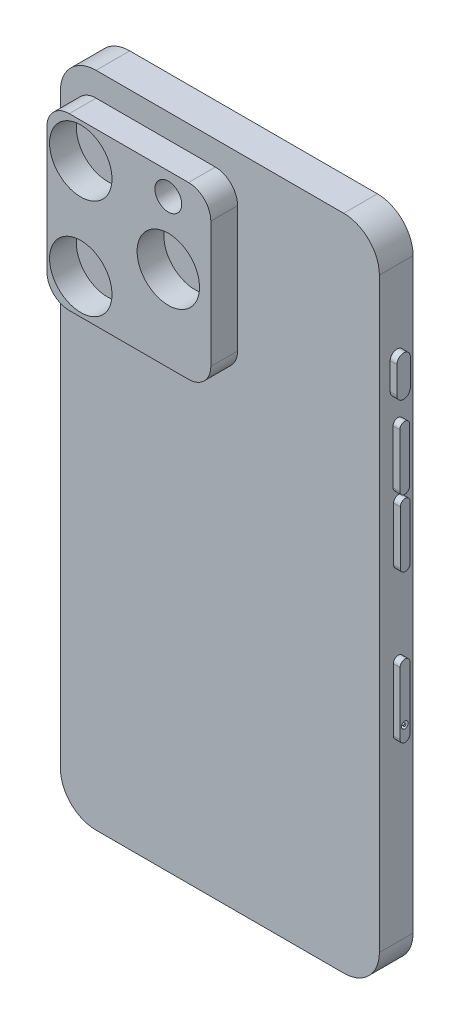
SolidWorks part; units mm, degrees
ref_plane "Front Plane" through (0, 0, 0) normal (0, 0, 1) x (1, 0, 0)
ref_plane "Top Plane" through (0, 0, 0) normal (0, 1, 0) x (1, 0, 0)
ref_plane "Right Plane" through (0, 0, 0) normal (1, 0, 0) x (0, 0, -1)
sketch "Sketch2" plane through (0, 0, 0) normal (0, 0, 1) x (1, 0, 0)
  line L1 (-27.75, 73.75) -> (27.75, 73.75)
  line L2 (-35.75, 65.75) -> (-35.75, -65.75)
  line L3 (-27.75, -73.75) -> (27.75, -73.75)
  line L4 (35.75, 65.75) -> (35.75, -65.75)
  line L5 (-35.75, 73.75) -> (35.75, -73.75) construction
  line L6 (-35.75, -73.75) -> (35.75, 73.75) construction
  arc A0 (27.75, -73.75) -> (35.75, -65.75) centre (27.75, -65.75) ccw
  arc A1 (-35.75, -65.75) -> (-27.75, -73.75) centre (-27.75, -65.75) ccw
  arc A2 (27.75, 73.75) -> (35.75, 65.75) centre (27.75, 65.75) cw
  arc A3 (-27.75, 73.75) -> (-35.75, 65.75) centre (-27.75, 65.75) ccw
  point P0 (0, 0)
  dimension "D3" = 8
  dimension "D1" = 147.5
  dimension "D2" = 71.5
extrude "Boss-Extrude1" add sketch "Sketch2" along normal blind 7.55
sketch "Sketch4" plane through (0, 0, 7.55) normal (0, 0, 1) x (1, 0, 0)
  line L0 (35.75, -65.75) -> (35.75, 65.75) construction
  line L1 (-27.7559, 68.3423) -> (-1.0259, 68.3423)
  line L2 (-32.7559, 63.3423) -> (-32.7559, 35.1323)
  line L3 (-27.7559, 30.1323) -> (-1.0259, 30.1323)
  line L4 (3.9741, 63.3423) -> (3.9741, 35.1323)
  line L5 (-32.7559, 68.3423) -> (3.9741, 30.1323) construction
  line L6 (-32.7559, 30.1323) -> (3.9741, 68.3423) construction
  line L7 (27.75, 73.75) -> (-27.75, 73.75) construction
  line L9 (-27.8059, 68.4423) -> (-0.9759, 68.4423)
  line L10 (-32.8059, 63.4423) -> (-32.8059, 35.0323)
  line L11 (-27.8059, 30.0323) -> (-0.9759, 30.0323)
  line L12 (4.0241, 63.4423) -> (4.0241, 35.0323)
  line L13 (-32.8059, 68.4423) -> (4.0241, 30.0323) construction
  line L14 (-32.8059, 30.0323) -> (4.0241, 68.4423) construction
  line L15 (-27.8559, 68.5423) -> (-0.9259, 68.5423)
  line L16 (-32.8559, 63.5423) -> (-32.8559, 34.9323)
  line L17 (-27.8559, 29.9323) -> (-0.9259, 29.9323)
  line L18 (4.0741, 63.5423) -> (4.0741, 34.9323)
  line L19 (-32.8559, 68.5423) -> (4.0741, 29.9323) construction
  line L20 (-32.8559, 29.9323) -> (4.0741, 68.5423) construction
  arc A0 (-1.0259, 30.1323) -> (3.9741, 35.1323) centre (-1.0259, 35.1323) ccw
  arc A1 (-32.7559, 35.1323) -> (-27.7559, 30.1323) centre (-27.7559, 35.1323) ccw
  arc A2 (-27.7559, 68.3423) -> (-32.7559, 63.3423) centre (-27.7559, 63.3423) ccw
  arc A3 (-1.0259, 68.3423) -> (3.9741, 63.3423) centre (-1.0259, 63.3423) cw
  circle A4 centre (-25.1701, 60.4509) radius 7
  circle A5 centre (-25.1701, 38.0236) radius 7
  circle A6 centre (-5.5508, 49.2373) radius 7
  circle A7 centre (-25.1701, 60.4509) radius 6
  circle A8 centre (-25.1701, 38.0236) radius 7
  circle A9 centre (-5.5508, 49.2373) radius 6
  circle A10 centre (-25.1701, 38.0236) radius 6
  circle A11 centre (-5.5508, 63.3423) radius 3
  arc A12 (-32.8559, 34.9323) -> (-27.8559, 29.9323) centre (-27.8559, 34.9323) ccw
  arc A13 (-32.8059, 35.0323) -> (-27.8059, 30.0323) centre (-27.8059, 35.0323) ccw
  arc A14 (-27.8559, 68.5423) -> (-32.8559, 63.5423) centre (-27.8559, 63.5423) ccw
  arc A15 (-27.8059, 68.4423) -> (-32.8059, 63.4423) centre (-27.8059, 63.4423) ccw
  arc A16 (-0.9259, 68.5423) -> (4.0741, 63.5423) centre (-0.9259, 63.5423) cw
  arc A17 (-0.9759, 68.4423) -> (4.0241, 63.4423) centre (-0.9759, 63.4423) cw
  arc A18 (-0.9759, 30.0323) -> (4.0241, 35.0323) centre (-0.9759, 35.0323) ccw
  arc A19 (-0.9259, 29.9323) -> (4.0741, 34.9323) centre (-0.9259, 34.9323) ccw
  point P0 (-14.3909, 49.2373)
  point P32 (-14.3909, 49.2373)
  point P38 (-14.3909, 49.2373)
  dimension "D3" = 5
  dimension "D4" = 14
  dimension "D5" = 14
  dimension "D6" = 14
  dimension "D7" = 12
  dimension "D8" = 12
  dimension "D9" = 12
  dimension "D10" = 6
  dimension "D15" = 5
  dimension "D1" = 36.73
  dimension "D2" = 38.21
  dimension "D11" = 38.41
  dimension "D12" = 36.83
  dimension "D13" = 38.61
  dimension "D14" = 36.93
extrude "Boss-Extrude2" add sketch "Sketch4" along normal blind 6.01 contours A3 L1 A2 L2 A1 L3 A0 L4 A11 A6 A5 A4
sketch "Sketch5" plane through (0, 0, 0) normal (0, 0, -1) x (-1, 0, 0)
  line L0 (0.1269, 66.9175) -> (-6.3731, 66.9175) construction
  line L1 (0.1269, 64.0393) -> (-6.3731, 64.0393)
  line L2 (0.1269, 69.7956) -> (-6.3731, 69.7956)
  arc A0 (0.1269, 64.0393) -> (0.1269, 69.7956) centre (0.1269, 66.9175) ccw
  arc A1 (-6.3731, 69.7956) -> (-6.3731, 64.0393) centre (-6.3731, 66.9175) ccw
  circle A2 centre (8.0178, 66.9175) radius 3.25
  circle A3 centre (8.0178, 66.9175) radius 2.25
  circle A4 centre (0.1269, 66.9175) radius 2.25
  circle A5 centre (-6.3731, 66.9175) radius 2.25
  point P2 (-3.1231, 66.9175)
  dimension "D2" = 6.5
  dimension "D3" = 4.5
  dimension "D4" = 4.5
  dimension "D5" = 4.5
  dimension "D1" = 6.5
extrude "Cut-Extrude1" cut sketch "Sketch5" against normal blind 0.5
sketch "Sketch6" plane through (-35.75, 0, 0) normal (-1, 0, 0) x (0, 0, 1)
  line L0 (3.317, 15.75) -> (3.317, 31.75) construction
  line L1 (1.817, 15.75) -> (1.817, 31.75)
  line L2 (4.817, 15.75) -> (4.817, 31.75)
  line L4 (7.55, 73.75) -> (0, 73.75) construction
  line L5 (3.317, -31.25) -> (3.317, -11.25) construction
  line L6 (1.817, -31.25) -> (1.817, -11.25)
  line L7 (4.817, -31.25) -> (4.817, -11.25)
  arc A0 (1.817, 15.75) -> (4.817, 15.75) centre (3.317, 15.75) ccw
  arc A1 (4.817, 31.75) -> (1.817, 31.75) centre (3.317, 31.75) ccw
  arc A2 (1.817, -31.25) -> (4.817, -31.25) centre (3.317, -31.25) ccw
  arc A3 (4.817, -11.25) -> (1.817, -11.25) centre (3.317, -11.25) ccw
  point P2 (3.317, 23.75)
  point P11 (3.317, -21.25)
  point P16 (0, 0)
  point P17 (0, 0)
  point P18 (0, 0)
  dimension "D5" = 1.5
  dimension "D6" = 1.5
  dimension "D1" = 16
  dimension "D2" = 50
  dimension "D3" = 20
  dimension "D4" = 45
extrude "Boss-Extrude3" add sketch "Sketch6" along normal blind 1.15
ref_plane "Plane2" through (36.25, 0, 0) normal (1, 0, 0) x (0, 0, -1)
sketch "Sketch11" plane through (35.75, 0, 0) normal (1, 0, 0) x (0, 0, -1)
  line L0 (-3.6201, 47.9186) -> (-3.6201, 41.9186) construction
  line L1 (-2.111, 47.9186) -> (-2.111, 41.9186)
  line L2 (-5.1293, 47.9186) -> (-5.1293, 41.9186)
  line L3 (-3.6201, 84.87) -> (-3.6201, -79.3485) construction
  arc A0 (-2.111, 47.9186) -> (-5.1293, 47.9186) centre (-3.6201, 47.9186) ccw
  arc A1 (-5.1293, 41.9186) -> (-2.111, 41.9186) centre (-3.6201, 41.9186) ccw
  point P2 (-3.6201, 44.9186)
  dimension "D1" = 6
extrude "Boss-Extrude4" add sketch "Sketch11" along normal blind 1.5
sketch "Sketch12" plane through (35.75, 0, 0) normal (1, 0, 0) x (0, 0, -1)
  line L0 (-3.3753, 34.9311) -> (-3.3753, 22.9311) construction
  line L1 (-2.2753, 34.9311) -> (-2.2753, 22.9311)
  line L2 (-4.4753, 34.9311) -> (-4.4753, 22.9311)
  line L3 (-3.3753, 73.5111) -> (-29.6523, 73.5111) construction
  arc A0 (-2.2753, 34.9311) -> (-4.4753, 34.9311) centre (-3.3753, 34.9311) ccw
  arc A1 (-4.4753, 22.9311) -> (-2.2753, 22.9311) centre (-3.3753, 22.9311) ccw
  point P2 (-3.3753, 28.9311)
  dimension "D1" = 1.1
  dimension "D2" = 12
  dimension "D3" = 44.58
extrude "Boss-Extrude5" add sketch "Sketch12" along normal blind 1.5
sketch "Sketch13" plane through (35.75, 0, 0) normal (1, 0, 0) x (0, 0, -1)
  line L0 (-3.2605, 19.9095) -> (-3.2605, 7.9095) construction
  line L1 (-2.1605, 19.9095) -> (-2.1605, 7.9095)
  line L2 (-4.3605, 19.9095) -> (-4.3605, 7.9095)
  arc A0 (-2.1605, 19.9095) -> (-4.3605, 19.9095) centre (-3.2605, 19.9095) ccw
  arc A1 (-4.3605, 7.9095) -> (-2.1605, 7.9095) centre (-3.2605, 7.9095) ccw
  point P3 (-3.2605, 13.9095)
  dimension "D2" = 1.1
  dimension "D1" = 12
extrude "Boss-Extrude6" add sketch "Sketch13" along normal blind 1.5
sketch "Sketch14" plane through (35.75, 0, 0) normal (1, 0, 0) x (0, 0, -1)
  line L0 (-3.317, -11.25) -> (-3.317, -25.25) construction
  line L1 (-2.217, -11.25) -> (-2.217, -25.25)
  line L2 (-4.417, -11.25) -> (-4.417, -25.25)
  arc A0 (-2.217, -11.25) -> (-4.417, -11.25) centre (-3.317, -11.25) ccw
  arc A1 (-4.417, -25.25) -> (-2.217, -25.25) centre (-3.317, -25.25) ccw
  point P3 (-3.317, -18.25)
  dimension "D2" = 1.1
  dimension "D1" = 14
extrude "Boss-Extrude7" add sketch "Sketch14" along normal blind 1.5
sketch "Sketch15" plane through (35.75, 0, 0) normal (1, 0, 0) x (0, 0, -1)
  circle A0 centre (-3.3387, -22.9217) radius 0.75
  circle A1 centre (-3.3387, -22.9217) radius 0.2825
  dimension "D1" = 1.5
extrude "Cut-Extrude2" cut sketch "Sketch15" along normal through all
sketch "Sketch16" plane through (0, -73.75, 0) normal (0, -1, 0) x (1, 0, 0)
  line L0 (-3.7764, 3.3433) -> (2.2236, 3.3433)
  line L1 (2.2236, 3.3433) -> (3.2236, 2.3433)
  line L2 (3.2236, 2.3433) -> (-4.7764, 2.3433)
  line L3 (-4.7764, 2.3433) -> (-3.7764, 3.3433)
  circle A0 centre (-6.6441, 2.9037) radius 1
  circle A1 centre (5.1807, 2.9037) radius 1
  circle A2 centre (-12.0862, 2.8876) radius 1
  circle A3 centre (-15.0862, 2.8876) radius 1
  circle A4 centre (-18.0862, 2.8876) radius 1
  circle A5 centre (-21.0862, 2.8876) radius 1
  circle A6 centre (5.1807, 2.9037) radius 0.8401
  circle A7 centre (-6.6441, 2.8876) radius 0.9027
  circle A8 centre (24.7875, 2.9037) radius 1
  circle A9 centre (21.7875, 2.9037) radius 1
  circle A10 centre (18.7875, 2.9037) radius 1
  circle A11 centre (15.7875, 2.9037) radius 1
  circle A12 centre (12.7875, 2.9037) radius 1
  circle A13 centre (9.7875, 2.9037) radius 1
  dimension "D2" = 2
  dimension "D3" = 2
  dimension "D4" = 2
  dimension "D5" = 8
  dimension "D6" = 6
  dimension "D7" = 45
  dimension "D8" = 45
  dimension "D9" = 0.5605
  dimension "D10" = 0.5605
  dimension "D1" = 4
  dimension "D11" = 6
extrude "Cut-Extrude3" cut sketch "Sketch16" against normal blind 1.5
